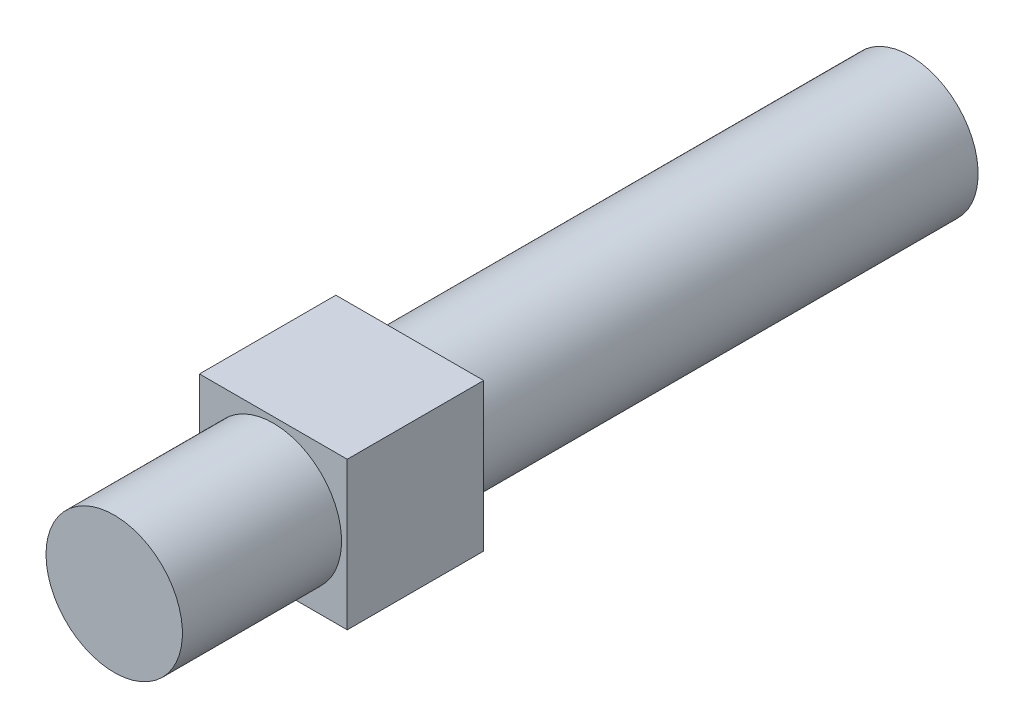
SolidWorks part; units mm, degrees
ref_plane "Front Plane" through (0, 0, 0) normal (0, 0, 1) x (1, 0, 0)
ref_plane "Top Plane" through (0, 0, 0) normal (0, 1, 0) x (1, 0, 0)
ref_plane "Right Plane" through (0, 0, 0) normal (1, 0, 0) x (0, 0, -1)
sketch "Sketch1" plane through (0, 0, 0) normal (0, 1, 0) x (1, 0, 0)
  line L0 (0, 75.2136) -> (0, -4.3003) construction
  line L1 (6, 0) -> (6, 70)
  line L2 (6, 70) -> (0, 70)
  line L3 (0, 0) -> (6, 0)
  line L4 (0, 70) -> (0, 0)
  dimension "D1" = 70
  dimension "D2" = 6
revolve "Revolve1" add sketch "Sketch1" angle 360 about L0
ref_plane "Plane1" through (0, 0, -14) normal (0, 0, 1) x (1, 0, 0)
sketch "Sketch2" plane through (0, 0, -14) normal (0, 0, 1) x (1, 0, 0)
  line L1 (6.5, 6.5) -> (-6.5, 6.5)
  line L2 (6.5, 6.5) -> (6.5, -6.5)
  line L3 (6.5, -6.5) -> (-6.5, -6.5)
  line L4 (-6.5, 6.5) -> (-6.5, -6.5)
  line L5 (6.5, 6.5) -> (-6.5, -6.5) construction
  line L6 (6.5, -6.5) -> (-6.5, 6.5) construction
  point P0 (0, 0)
  dimension "D1" = 13
  dimension "D2" = 13
extrude "Boss-Extrude1" add sketch "Sketch2" against normal blind 12
